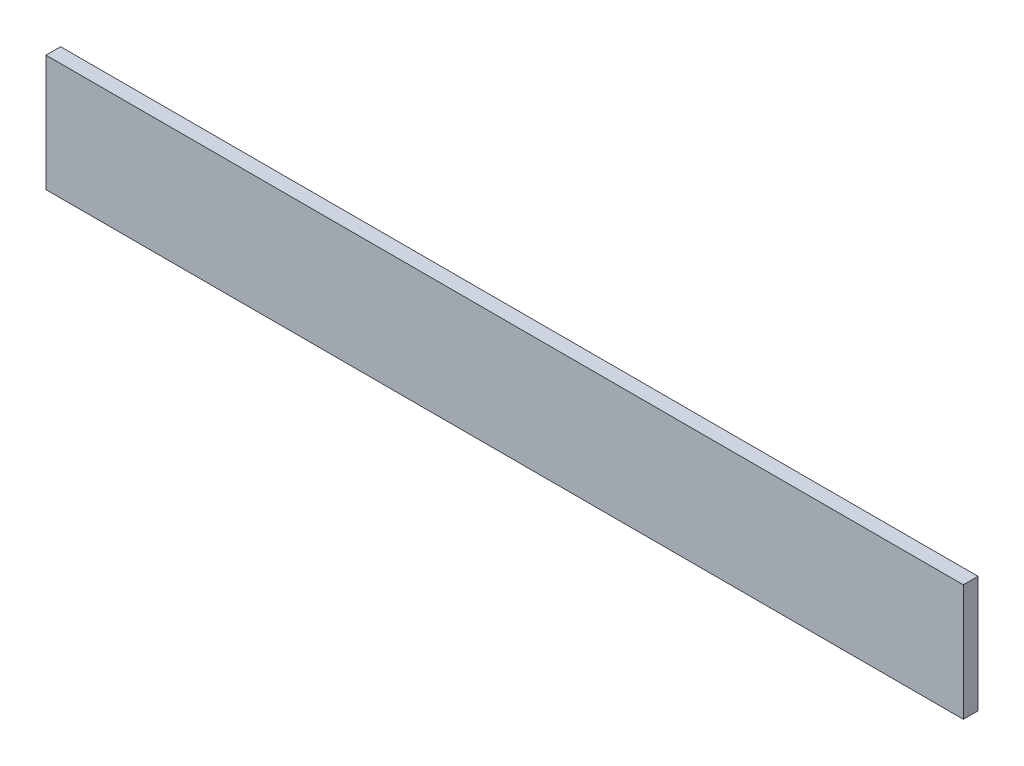
SolidWorks part; units mm, degrees
ref_plane "Front" through (0, 0, 0) normal (0, 0, 1) x (1, 0, 0)
ref_plane "Top" through (0, 0, 0) normal (0, 1, 0) x (1, 0, 0)
ref_plane "Right" through (0, 0, 0) normal (1, 0, 0) x (0, 0, -1)
sketch "Sketch1" plane through (0, 0, 0) normal (1, 0, 0) x (0, 0, -1)
  line L1 (0, 0) -> (0.8, 0)
  line L2 (0, 0) -> (0, 6.35)
  line L3 (0, 6.35) -> (0.8, 6.35)
  line L4 (0.8, 0) -> (0.8, 6.35)
  dimension "D1" = 0.8
  dimension "D2" = 6.35
extrude "Boss-Extrude1" add sketch "Sketch1" along normal blind 50
